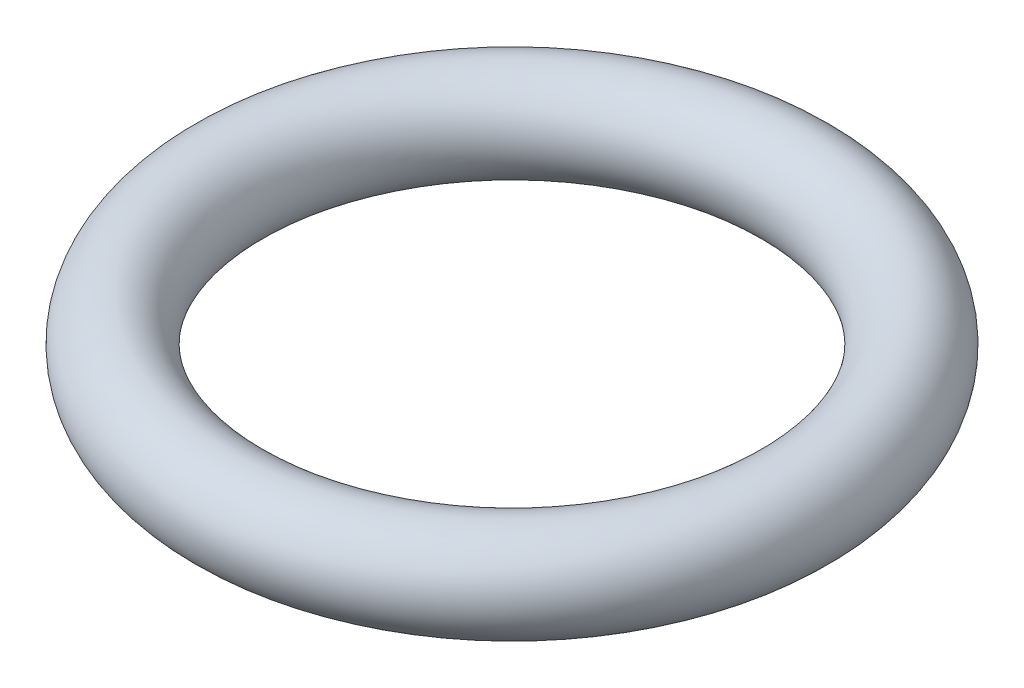
SolidWorks part; units mm, degrees
ref_plane "Front" through (0, 0, 0) normal (0, 0, 1) x (1, 0, 0)
ref_plane "Top" through (0, 0, 0) normal (0, 1, 0) x (1, 0, 0)
ref_plane "Right" through (0, 0, 0) normal (1, 0, 0) x (0, 0, -1)
sketch "Sketch1" plane through (0, 0, 0) normal (1, 0, 0) x (0, 0, -1)
  line L0 (0, -77.3311) -> (0, 77.3311) construction
  circle A0 centre (-152.4, 0) radius 25.4
  point P4 (0, 0)
  dimension "D1" = 50.8
  dimension "D2" = 254
  dimension "D3" = 355.6
revolve "Revolve1" add sketch "Sketch1" angle 360 about L0
